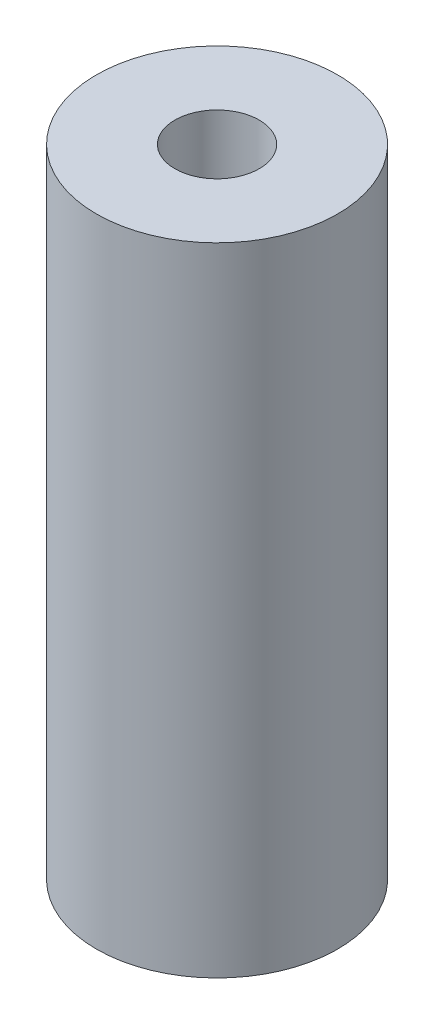
SolidWorks part; units mm, degrees
ref_plane "Front Plane" through (0, 0, 0) normal (0, 0, 1) x (1, 0, 0)
ref_plane "Top Plane" through (0, 0, 0) normal (0, 1, 0) x (1, 0, 0)
ref_plane "Right Plane" through (0, 0, 0) normal (1, 0, 0) x (0, 0, -1)
sketch "Sketch1" plane through (0, 0, 0) normal (0, 1, 0) x (1, 0, 0)
  circle A0 centre (0, 0) radius 5
  circle A1 centre (0, 0) radius 1.75
  point P3 (0, 0)
  dimension "D1" = 10
  dimension "D2" = 3.5
extrude "Boss-Extrude1" add sketch "Sketch1" along normal blind 26.4
